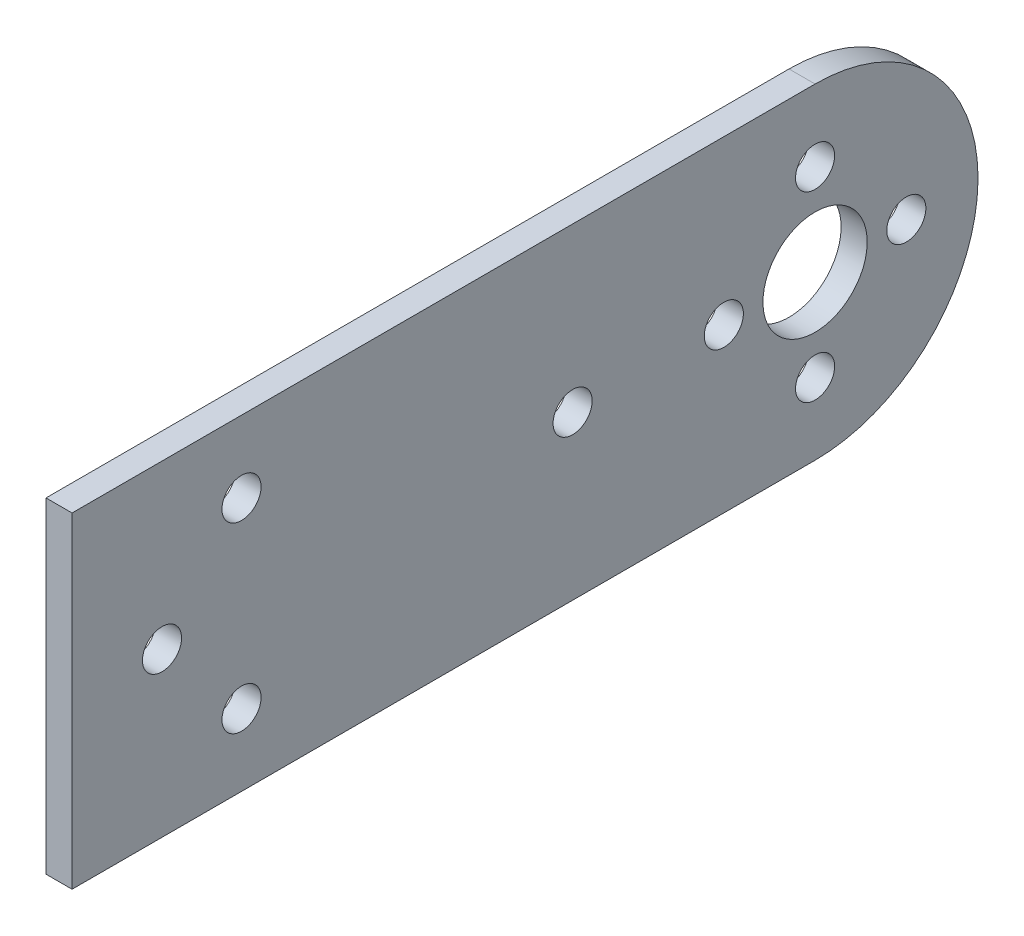
SolidWorks part; units mm, degrees
ref_plane "前视基准面" through (0, 0, 0) normal (0, 0, 1) x (1, 0, 0)
ref_plane "上视基准面" through (0, 0, 0) normal (0, 1, 0) x (1, 0, 0)
ref_plane "右视基准面" through (0, 0, 0) normal (1, 0, 0) x (0, 0, -1)
other "Configuration Table"
sketch "草图1" plane through (0, 0, 0) normal (0, 0, 1) x (1, 0, 0)
  line L1 (-1, 12.5) -> (1, 12.5)
  line L2 (-1, 12.5) -> (-1, -12.5)
  line L3 (-1, -12.5) -> (1, -12.5)
  line L4 (1, 12.5) -> (1, -12.5)
  line L5 (-1, 12.5) -> (1, -12.5) construction
  line L6 (-1, -12.5) -> (1, 12.5) construction
  point P0 (0, 0)
  dimension "D1" = 2
  dimension "D2" = 25
extrude "凸台-拉伸1" add sketch "草图1" along normal blind 69.5
sketch "草图2" plane through (1, 0, 0) normal (1, 0, 0) x (0, 0, -1)
  line L0 (-76.9231, 0) -> (27.7328, 0) construction
  line L1 (-44.4991, 0) -> (0, 0) construction
  line L2 (-69.5, -12.5) -> (-69.5, 12.5) construction
  line L3 (-12.4991, 12.5) -> (0, 12.5)
  line L4 (0, 12.5) -> (0, -12.5)
  line L5 (0, -12.5) -> (-12.4991, -12.5)
  circle A0 centre (-12.4991, 0) radius 7 construction
  circle A1 centre (-12.4991, 7) radius 1.5
  circle A2 centre (-5.4991, 0) radius 1.5
  circle A3 centre (-12.4991, -7) radius 1.5
  circle A4 centre (-19.4991, 0) radius 1.5
  circle A5 centre (-12.4991, 0) radius 4
  circle A6 centre (-31.0991, 0) radius 1.5
  arc A7 (-12.4991, -12.5) -> (-12.4991, 12.5) centre (-12.4991, 0) ccw
  circle A8 centre (-62.6, 0) radius 1.55
  line M2 (0, -12.5) -> (0, 12.5)
  line M3 (0, 12.5) -> (-69.5, 12.5)
  line M5 (-69.5, -12.5) -> (0, -12.5)
  dimension "D1" = 14
  dimension "D2" = 8
  dimension "D3" = 3
  dimension "D5" = 12.5
  dimension "D7" = 3.1
  dimension "D4" = 18.6
  dimension "D6" = 6.9
extrude "切除-拉伸2" cut sketch "草图2" against normal blind 69.5 contours A7 M2 M3 | A7 M5 M2 | A2 | A1 | A3 | A4 | A5 | A6
sketch "草图4" plane through (1, 0, 0) normal (1, 0, 0) x (0, 0, -1)
  line L0 (-79.5281, 0) -> (12.4173, 0) construction
  line L1 (-69.5, -12.5) -> (-69.5, 12.5) construction
  line L2 (-12.4991, 7) -> (-74.3107, 7) construction
  circle A0 centre (-62.6, 0) radius 1.5
  circle A1 centre (-56.5, 7) radius 1.5
  circle A2 centre (-56.5, -7) radius 1.5
  point P11 (0, 0)
  dimension "D2" = 3
  dimension "D4" = 3
  dimension "D1" = 6.9
  dimension "D3" = 13
extrude "切除-拉伸3" cut sketch "草图4" against normal blind 10
